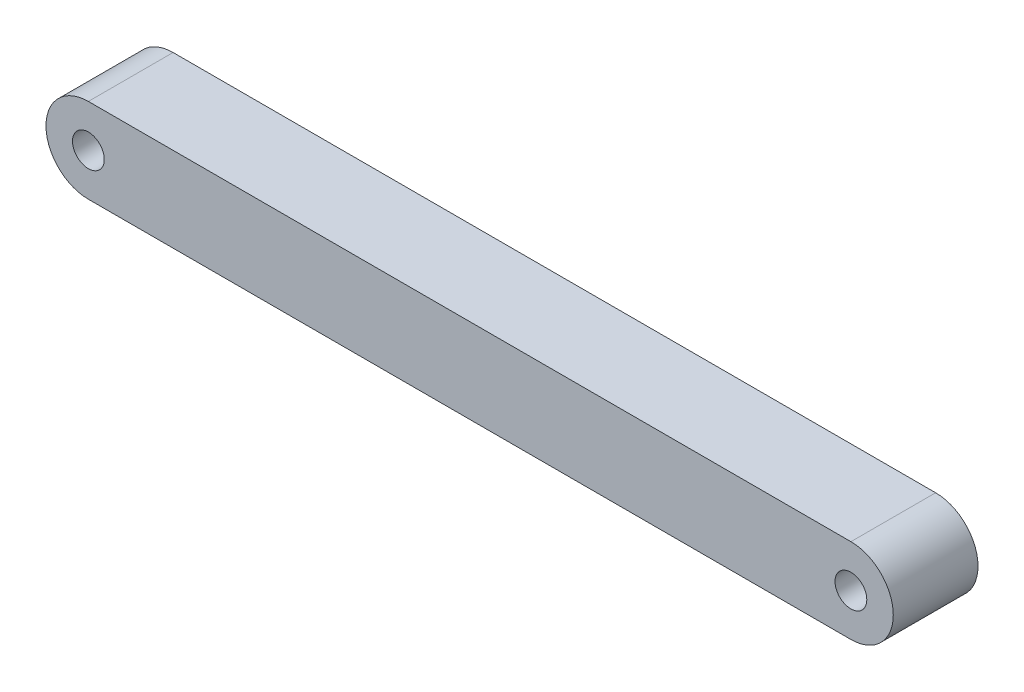
SolidWorks part; units mm, degrees
ref_plane "Front Plane" through (0, 0, 0) normal (0, 0, 1) x (1, 0, 0)
ref_plane "Top Plane" through (0, 0, 0) normal (0, 1, 0) x (1, 0, 0)
ref_plane "Right Plane" through (0, 0, 0) normal (1, 0, 0) x (0, 0, -1)
sketch "Sketch1" plane through (0, 0, 0) normal (0, 0, 1) x (1, 0, 0)
  line L0 (-36, 0) -> (36, 0) construction
  line L1 (-36, 4) -> (36, 4)
  line L2 (-36, -4) -> (36, -4)
  arc A0 (-36, 4) -> (-36, -4) centre (-36, 0) ccw
  arc A1 (36, -4) -> (36, 4) centre (36, 0) ccw
  circle A2 centre (36, 0) radius 1.5
  circle A3 centre (-36, 0) radius 1.5
  point P3 (0, 0)
  dimension "D3" = 4
  dimension "D4" = 3
  dimension "D5" = 3
  dimension "D1" = 72
  dimension "D2" = 36
extrude "Boss-Extrude1" add sketch "Sketch1" along normal blind 8
